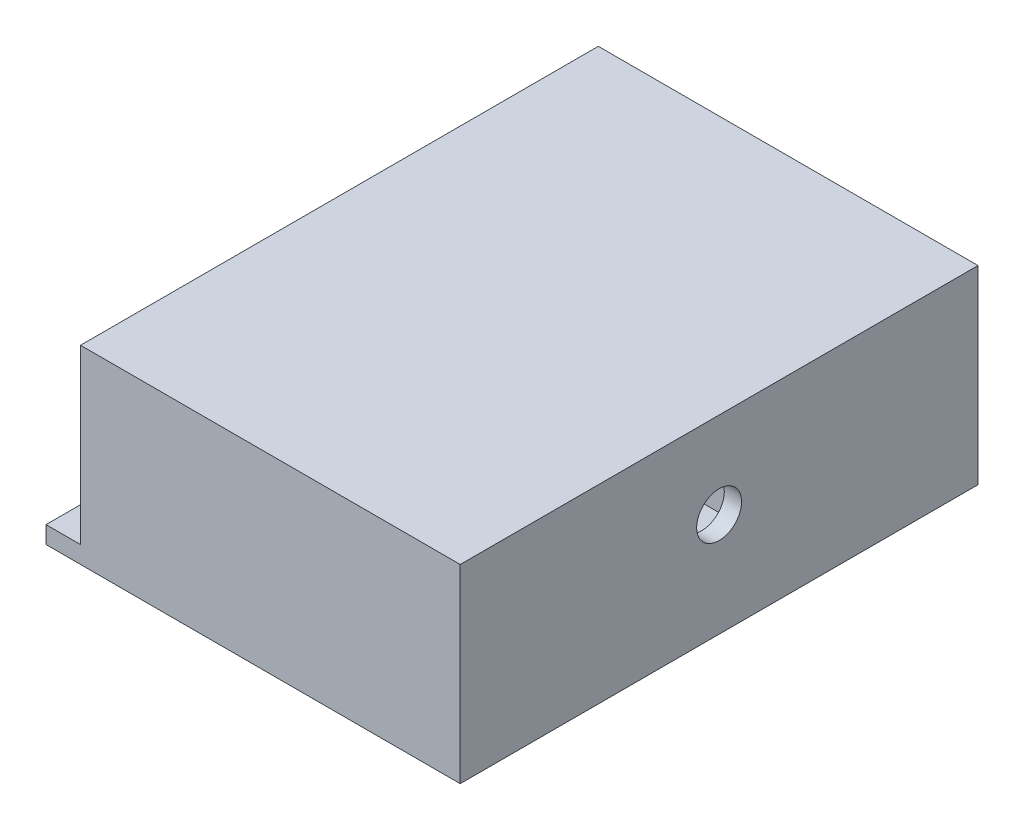
SolidWorks part; units mm, degrees
ref_plane "Front Plane" through (0, 0, 0) normal (0, 0, 1) x (1, 0, 0)
ref_plane "Top Plane" through (0, 0, 0) normal (0, 1, 0) x (1, 0, 0)
ref_plane "Right Plane" through (0, 0, 0) normal (1, 0, 0) x (0, 0, -1)
sketch "Sketch3" plane through (0, 0, 0) normal (0, 1, 0) x (1, 0, 0)
  line L1 (0, 0) -> (120, 0)
  line L2 (0, 0) -> (0, 150)
  line L3 (0, 150) -> (120, 150)
  line L4 (120, 0) -> (120, 150)
  dimension "D1" = 120
  dimension "D2" = 150
extrude "Boss-Extrude2" add sketch "Sketch3" along normal blind 5
sketch "Sketch4" plane through (0, 5, 0) normal (0, 1, 0) x (1, 0, 0)
  line L0 (10, 0) -> (10, 5)
  line L1 (0, 0) -> (120, 0) construction
  line L2 (10, 5) -> (115, 5)
  line L3 (115, 5) -> (115, 145)
  line L4 (115, 145) -> (10, 145)
  line L5 (10, 145) -> (10, 150)
  line L6 (120, 150) -> (0, 150) construction
  line L7 (10, 150) -> (120, 150)
  line L8 (120, 150) -> (120, 0)
  line L9 (120, 0) -> (10, 0)
  line L10 (0, 150) -> (0, 0) construction
  point P16 (10, 147.5)
  point P17 (10, 2.5)
  dimension "D1" = 10
  dimension "D2" = 10
  dimension "D3" = 5
  dimension "D4" = 2.5
  dimension "D5" = 5
extrude "Boss-Extrude3" add sketch "Sketch4" along normal blind 45
sketch "Sketch5" plane through (0, 50, 0) normal (0, 1, 0) x (1, 0, 0)
  line L1 (10, 150) -> (120, 150)
  line L2 (10, 150) -> (10, 0)
  line L3 (10, 0) -> (120, 0)
  line L4 (120, 150) -> (120, 0)
extrude "Boss-Extrude4" add sketch "Sketch5" along normal blind 5
sketch "Sketch6" plane through (120, 0, 0) normal (1, 0, 0) x (0, 0, -1)
  line L0 (0, 55) -> (0, 0) construction
  line L1 (0, 0) -> (150, 0) construction
  circle A0 centre (75, 30) radius 6.5
  dimension "D1" = 13
  dimension "D2" = 75
  dimension "D3" = 30
extrude "Cut-Extrude1" cut sketch "Sketch6" against normal blind 5
sketch "Sketch7" plane through (0, 5, 0) normal (0, 1, 0) x (1, 0, 0)
  line L0 (115, 5) -> (10, 5) construction
  line L1 (115, 145) -> (75, 145)
  line L2 (115, 145) -> (115, 5)
  line L3 (115, 5) -> (75, 5)
  line L4 (75, 145) -> (75, 5)
  dimension "D1" = 40
extrude "Boss-Extrude5" add sketch "Sketch7" along normal blind 8
sketch "Sketch8" plane through (0, 13, 0) normal (0, 1, 0) x (1, 0, 0)
  line L0 (115, 5) -> (115, 145) construction
  line L1 (75, 52.5) -> (115, 52.5)
  line L2 (75, 52.5) -> (75, 57.5)
  line L3 (75, 57.5) -> (115, 57.5)
  line L4 (115, 52.5) -> (115, 57.5)
  line L5 (75, 145) -> (75, 5) construction
  line L6 (75, 97.5) -> (115, 97.5)
  line L7 (75, 97.5) -> (75, 92.5)
  line L8 (75, 92.5) -> (115, 92.5)
  line L9 (115, 97.5) -> (115, 92.5)
  line L10 (115, 145) -> (75, 145) construction
  line L11 (75, 5) -> (115, 5) construction
  dimension "D1" = 0
  dimension "D2" = 35
  dimension "D3" = 47.5
  dimension "D4" = 5
  dimension "D5" = 47.5
extrude "Boss-Extrude6" add sketch "Sketch8" along normal blind 25.5
sketch "Sketch9" plane through (10, 0, 0) normal (-1, 0, 0) x (0, 0, 1)
  line L0 (-150, 5) -> (-145, 5) construction
  line L1 (-5, 5) -> (0, 5) construction
  line L2 (-150, 55) -> (0, 55) construction
  line L3 (0, 55) -> (0, 5) construction
  line L4 (-150, 55) -> (-150, 5) construction
  circle A0 centre (-147.5, 10) radius 1.5
  circle A1 centre (-147.5, 52.5) radius 1.5
  circle A2 centre (-2.5, 10) radius 1.5
  circle A3 centre (-2.5, 52.5) radius 1.5
  dimension "D1" = 3
  dimension "D2" = 3
  dimension "D3" = 3
  dimension "D4" = 3
  dimension "D8" = 2.5
  dimension "D9" = 2.5
  dimension "D10" = 2.5
  dimension "D5" = 5
  dimension "D6" = 5
  dimension "D7" = 2.5
  dimension "D11" = 2.5
extrude "Cut-Extrude2" cut sketch "Sketch9" against normal blind 10
sketch "Sketch10" plane through (75, 0, 0) normal (-1, 0, 0) x (0, 0, 1)
  line L1 (-97.5, 13) -> (-145, 13)
  line L2 (-97.5, 13) -> (-97.5, 5)
  line L3 (-97.5, 5) -> (-145, 5)
  line L4 (-145, 13) -> (-145, 5)
  line L5 (-52.5, 13) -> (-5, 13)
  line L6 (-52.5, 13) -> (-52.5, 5)
  line L7 (-52.5, 5) -> (-5, 5)
  line L8 (-5, 13) -> (-5, 5)
extrude "Cut-Extrude3" cut sketch "Sketch10" against normal blind 40
sketch "Sketch11" plane through (75, 0, 0) normal (-1, 0, 0) x (0, 0, 1)
  line L1 (-97.5, 5) -> (-52.5, 5)
  line L2 (-97.5, 5) -> (-97.5, 38.5)
  line L3 (-97.5, 38.5) -> (-52.5, 38.5)
  line L4 (-52.5, 5) -> (-52.5, 38.5)
extrude "Cut-Extrude4" cut sketch "Sketch11" against normal up to surface (40 mm away) up to face at (115, 30, -81.5)
sketch "Sketch12" plane through (115, 0, 0) normal (-1, 0, 0) x (0, 0, 1)
  line L0 (-145, 5) -> (-5, 5) construction
  line L1 (-92.5, 5) -> (-36.5, 5)
  line L2 (-92.5, 5) -> (-92.5, 20)
  line L3 (-92.5, 20) -> (-36.5, 20)
  line L4 (-36.5, 5) -> (-36.5, 20)
  circle A0 centre (-75, 30) radius 6.5 construction
  dimension "D1" = 10
  dimension "D2" = 56
  dimension "D3" = 17.5
extrude "Boss-Extrude7" add sketch "Sketch12" along normal blind 40
sketch "Sketch13" plane through (115, 0, 0) normal (-1, 0, 0) x (0, 0, 1)
  line L1 (-92.5, 20) -> (-85.5, 20)
  line L2 (-92.5, 20) -> (-92.5, 40.5)
  line L3 (-92.5, 40.5) -> (-85.5, 40.5)
  line L4 (-85.5, 20) -> (-85.5, 40.5)
  line L5 (-36.5, 20) -> (-43.5, 20)
  line L6 (-36.5, 20) -> (-36.5, 40.5)
  line L7 (-36.5, 40.5) -> (-43.5, 40.5)
  line L8 (-43.5, 20) -> (-43.5, 40.5)
  dimension "D1" = 20.5
  dimension "D2" = 20.5
  dimension "D3" = 7
  dimension "D4" = 7
extrude "Boss-Extrude8" add sketch "Sketch13" along normal blind 11
sketch "Sketch14" plane through (115, 0, 0) normal (-1, 0, 0) x (0, 0, 1)
  line L1 (-36.5, 40.5) -> (-92.5, 40.5)
  line L2 (-36.5, 40.5) -> (-36.5, 45.5)
  line L3 (-36.5, 45.5) -> (-92.5, 45.5)
  line L4 (-92.5, 40.5) -> (-92.5, 45.5)
  dimension "D1" = 5
extrude "Boss-Extrude9" add sketch "Sketch14" along normal up to surface (11 mm away) up to face at (104, 30.25, -89)
